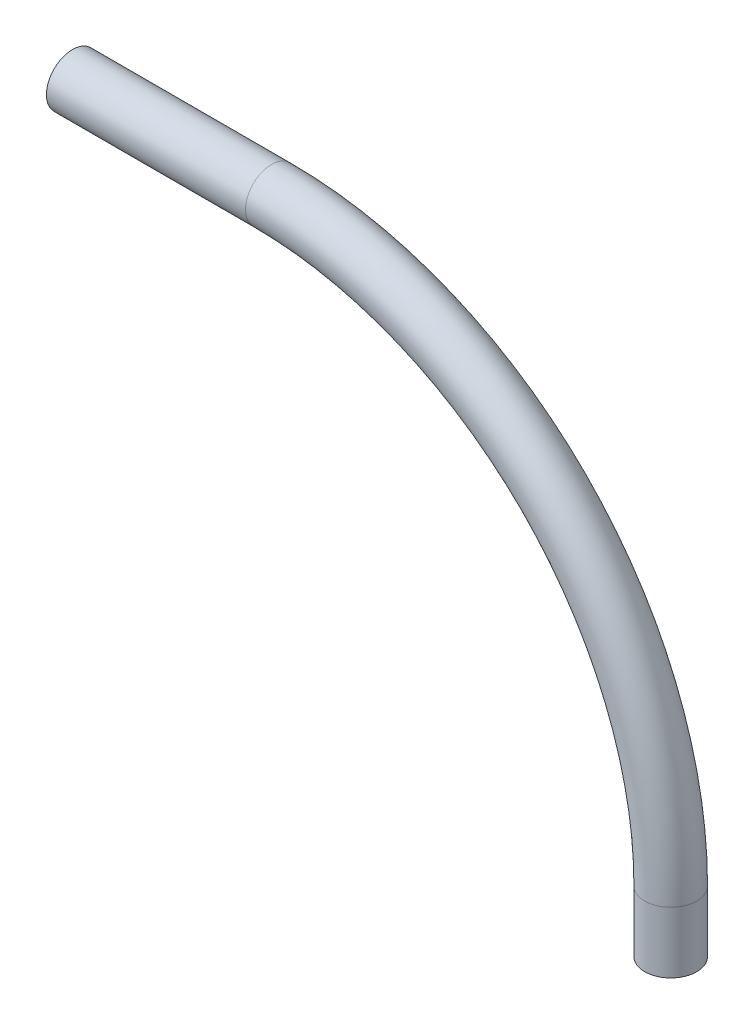
SolidWorks part; units mm, degrees
material "Polyethylene Cross-Linked"
ref_plane "Front Plane" through (0, 0, 0) normal (0, 0, 1) x (1, 0, 0)
ref_plane "Top Plane" through (0, 0, 0) normal (0, 1, 0) x (1, 0, 0)
ref_plane "Right Plane" through (0, 0, 0) normal (1, 0, 0) x (0, 0, -1)
sketch3d "3DSketch1"
  line L0 (-63.9533, 176.4423, 4.9176) -> (1.0467, 176.4423, 4.9176)
  line L1 (131.4267, 26.0623, 4.9176) -> (131.4267, 46.0623, 4.9176)
  circle A0 centre (131.4267, 26.0623, 4.9176) radius 7.5 construction
  circle A1 centre (-63.9533, 176.4423, 4.9176) radius 7.5 construction
  arc A2 (1.0467, 176.4423, 4.9176) -> (131.4267, 46.0623, 4.9176) centre (1.0467, 46.0623, 4.9176) ccw
  point P3 (131.4267, 33.5623, 4.9176)
  point P5 (-71.4533, 176.4423, 4.9176)
  point P9 (128.5615, 176.4423, 4.9176)
  point P10 (1.0467, 46.0623, -125.4624)
  dimension "D1" = 130.38
  dimension "D2" = 20
  dimension "D3" = 65
ref_plane "Plane1" through (-63.9533, 176.4423, 4.9176) normal (1, 0, 0) x (0, 0, -1)
sketch "Sketch2" plane through (-63.9533, 176.4423, 4.9176) normal (1, 0, 0) x (0, 0, -1)
  circle A0 centre (0, 0) radius 4.85
  circle A1 centre (0, 0) radius 8.5
  dimension "D1" = 9.7
  dimension "D2" = 17
sweep "Sweep1" add profiles "Sketch2" path "3DSketch1"
